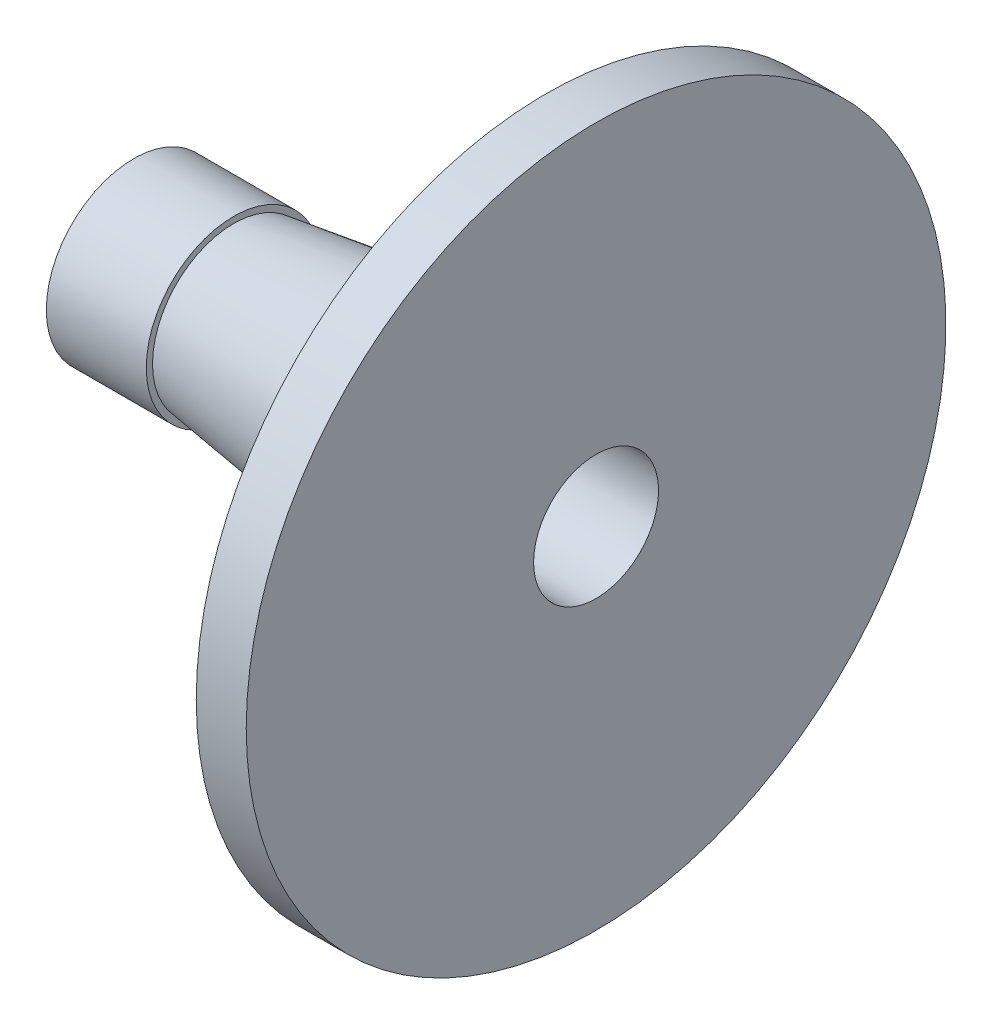
SolidWorks part; units mm, degrees
ref_plane "Front Plane" through (0, 0, 0) normal (0, 0, 1) x (1, 0, 0)
ref_plane "Top Plane" through (0, 0, 0) normal (0, 1, 0) x (1, 0, 0)
ref_plane "Right Plane" through (0, 0, 0) normal (1, 0, 0) x (0, 0, -1)
sketch "Sketch1" plane through (0, 0, 0) normal (0, 0, 1) x (1, 0, 0)
  line L0 (0, 0) -> (185, 0) construction
  line L1 (185, 25) -> (185, 140)
  line L2 (185, 140) -> (165, 140)
  line L3 (165, 140) -> (165, 50)
  line L4 (165, 50) -> (40, 32.5)
  line L5 (40, 32.5) -> (40, 35)
  line L6 (40, 35) -> (0, 35)
  line L7 (0, 35) -> (0, 25)
  line L8 (0, 25) -> (185, 25)
  point P3 (175, 140)
  point P7 (174.1505, 18.713)
  point P13 (174.1505, 18.5223)
  point P14 (0, 0)
  point P15 (91.9859, 140)
  point P16 (0, 0)
  point P17 (185, 0)
  dimension "D1" = 20
  dimension "D2" = 125
  dimension "D3" = 40
  dimension "D4" = 32.5
  dimension "D5" = 140
  dimension "D6" = 25
  dimension "D7" = 50
  dimension "D8" = 35
revolve "Revolve1" add sketch "Sketch1" angle 360 about L0
